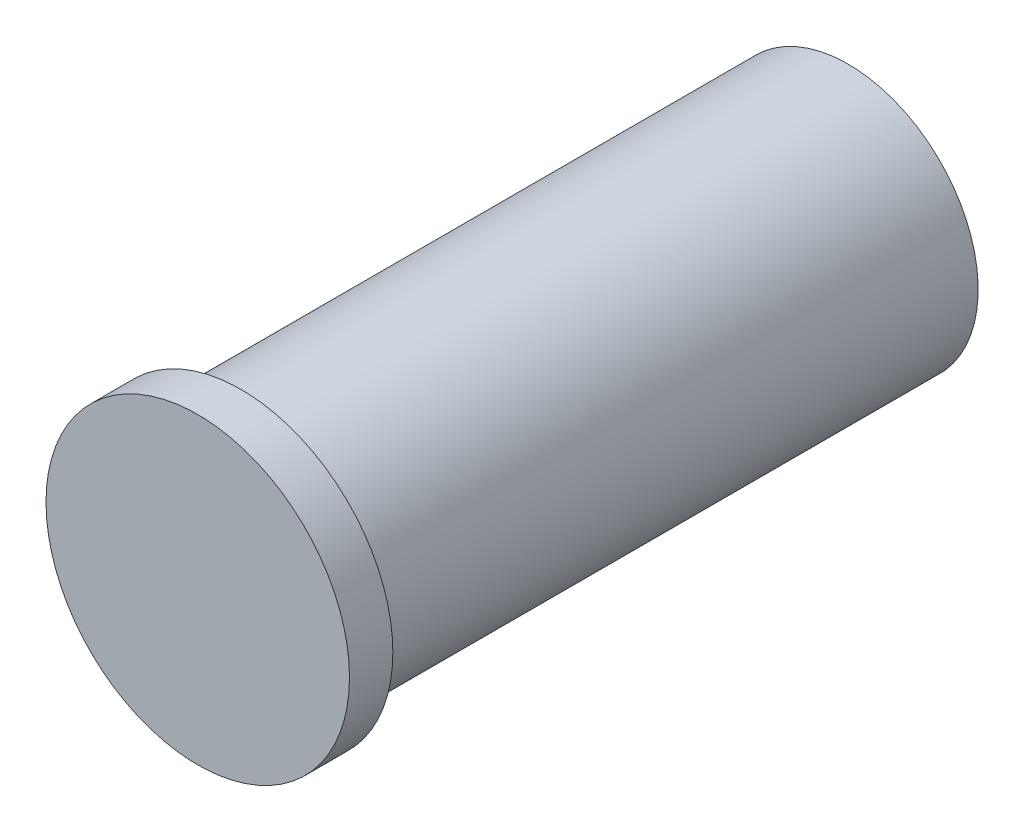
SolidWorks part; units mm, degrees
ref_plane "Alzado" through (0, 0, 0) normal (0, 0, 1) x (1, 0, 0)
ref_plane "Planta" through (0, 0, 0) normal (0, 1, 0) x (1, 0, 0)
ref_plane "Vista lateral" through (0, 0, 0) normal (1, 0, 0) x (0, 0, -1)
sketch "Sketch1" plane through (0, 0, 0) normal (0, 0, 1) x (1, 0, 0)
  circle A0 centre (0, 0) radius 1.5
extrude "Boss-Extrude1" add sketch "Sketch1" along normal blind 2
sketch "Sketch2" plane through (0, 0, 2) normal (0, 0, 1) x (1, 0, 0)
  circle A0 centre (0, 0) radius 1.75
extrude "Boss-Extrude2" add sketch "Sketch2" along normal blind 0.5
sketch "Sketch3" plane through (0, 0, 0) normal (0, 0, -1) x (-1, 0, 0)
  circle A0 centre (0, 0) radius 1.5
extrude "Boss-Extrude3" add sketch "Sketch3" along normal blind 5
